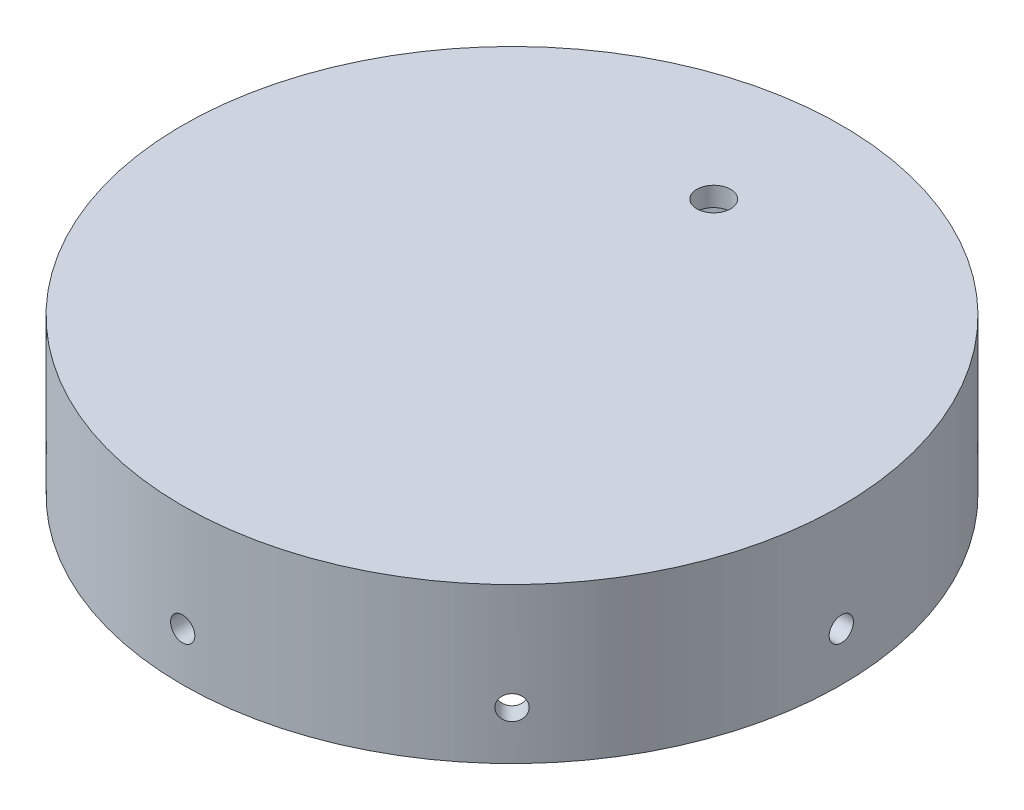
SolidWorks part; units mm, degrees
ref_plane "前视基准面" through (0, 0, 0) normal (0, 0, 1) x (1, 0, 0)
ref_plane "上视基准面" through (0, 0, 0) normal (0, 1, 0) x (1, 0, 0)
ref_plane "右视基准面" through (0, 0, 0) normal (1, 0, 0) x (0, 0, -1)
sketch "草图1" plane through (0, 0, 0) normal (0, 1, 0) x (1, 0, 0)
  circle A1 centre (0, 0) radius 34
  dimension "D2" = 68
extrude "凸台-拉伸1" add sketch "草图1" along normal blind 16
sketch "草图2" plane through (0, 0, 0) normal (0, 0, 1) x (1, 0, 0)
  line L0 (-34, 0) -> (34, 0) construction
  circle A0 centre (0, 5) radius 1.25
  dimension "D2" = 2.5
  dimension "D1" = 5
extrude "切除-拉伸1" cut sketch "草图2" against normal up to next
pattern_circular "阵列(圆周)1" count 8 every 45 about axis through (0, 16, 0) along (0, 1, 0) of "切除-拉伸1"
sketch "草图3" plane through (0, 0, 0) normal (0, 1, 0) x (1, 0, 0)
  circle A0 centre (0, 0) radius 32
  dimension "D1" = 64
extrude "切除-拉伸2" cut sketch "草图3" along normal blind 14
sketch "草图5" plane through (0, 0, 0) normal (0, 1, 0) x (1, 0, 0)
  line L0 (0, 0) -> (0, 34) construction
  circle A0 centre (0, 0) radius 34 construction
  circle A1 centre (0, 20.8148) radius 1.7488
  dimension "D1" = 3.4976
extrude "切除-拉伸3" cut sketch "草图5" along normal through all
